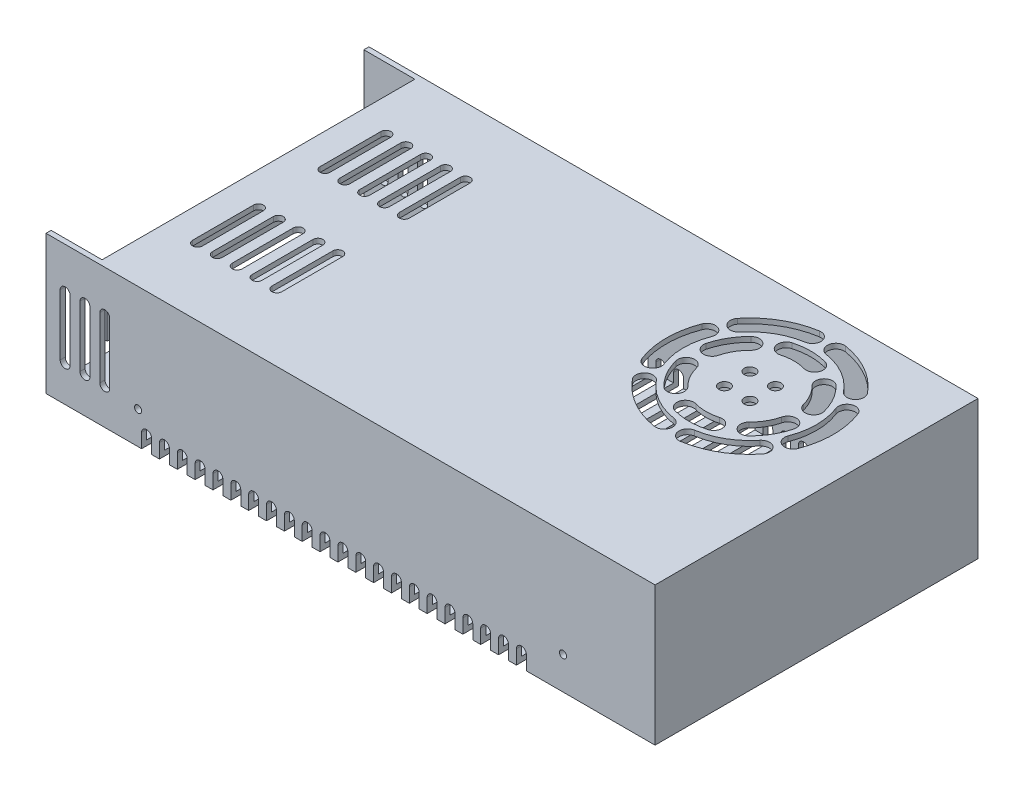
SolidWorks part; units mm, degrees
material "6061 Alloy"
ref_plane "Front Plane" through (0, 0, 0) normal (0, 0, 1) x (1, 0, 0)
ref_plane "Top Plane" through (0, 0, 0) normal (0, 1, 0) x (1, 0, 0)
ref_plane "Right Plane" through (0, 0, 0) normal (1, 0, 0) x (0, 0, -1)
sketch "Sketch1" plane through (0, 0, 0) normal (0, 1, 0) x (1, 0, 0)
  line L0 (-107.5, 55.2) -> (105.7, 55.2)
  line L1 (-107.5, -57) -> (107.5, -57)
  line L2 (-107.5, -57) -> (-107.5, -55.2)
  line L3 (-107.5, 57) -> (107.5, 57)
  line L4 (107.5, -57) -> (107.5, 57)
  line L5 (-107.5, -57) -> (107.5, 57) construction
  line L6 (-107.5, 57) -> (107.5, -57) construction
  line L7 (105.7, 55.2) -> (105.7, -55.2)
  line L8 (105.7, -55.2) -> (-107.5, -55.2)
  line L9 (-107.5, 55.2) -> (-107.5, 57)
  point P0 (0, 0)
  dimension "D1" = 114
  dimension "D2" = 215
  dimension "D3" = 1.8
  dimension "D4" = 1.8
  dimension "D5" = 1.8
extrude "Boss-Extrude1" add sketch "Sketch1" along normal blind 49
sketch "Sketch2" plane through (0, 0, 0) normal (0, 1, 0) x (1, 0, 0)
  line L0 (107.5, -57) -> (107.5, 57)
  line L1 (107.5, -57) -> (-107.5, -57)
  line L2 (107.5, 57) -> (-107.5, 57)
  line L3 (-107.5, -57) -> (-107.5, 57)
extrude "Boss-Extrude2" add sketch "Sketch2" along normal blind 1.8
sketch "Sketch3" plane through (0, 49, 0) normal (0, 1, 0) x (1, 0, 0)
  line L0 (107.5, 57) -> (107.5, -57)
  line L1 (107.5, 57) -> (-89.5, 57)
  line L2 (107.5, -57) -> (-89.5, -57)
  line L3 (-89.5, 57) -> (-89.5, -57)
  line L4 (-107.5, -55.2) -> (-107.5, -57) construction
  dimension "D1" = 18
extrude "Boss-Extrude3" add sketch "Sketch3" against normal blind 1.8
sketch "Sketch4" plane through (0, 49, 0) normal (0, 1, 0) x (1, 0, 0)
  line L0 (-89.5, 55.2) -> (-89.5, -55.2)
  line L1 (-89.5, 55.2) -> (-87.7, 55.2)
  line L2 (-89.5, -55.2) -> (-87.7, -55.2)
  line L3 (-87.7, 55.2) -> (-87.7, -55.2)
  dimension "D1" = 1.8
extrude "Boss-Extrude4" add sketch "Sketch4" against normal blind 24
sketch "Sketch5" plane through (0, 49, 0) normal (0, 1, 0) x (1, 0, 0)
  line L0 (-79.5, -11.75) -> (-79.5, -33.25)
  line L1 (-76, -33.25) -> (-76, -11.75)
  line L2 (-107.5, 0) -> (107.5, 0) construction
  line L3 (-107.5, 55.2) -> (-107.5, -55.2) construction
  line L4 (107.5, -57) -> (107.5, 57) construction
  line L5 (-89.5, 55.2) -> (-89.5, -55.2) construction
  line L6 (-72.5, -11.75) -> (-72.5, -33.25)
  line L7 (-69, -33.25) -> (-69, -11.75)
  line L8 (-65.5, -11.75) -> (-65.5, -33.25)
  line L9 (-62, -33.25) -> (-62, -11.75)
  line L10 (-58.5, -11.75) -> (-58.5, -33.25)
  line L11 (-55, -33.25) -> (-55, -11.75)
  line L12 (-51.5, -11.75) -> (-51.5, -33.25)
  line L13 (-48, -33.25) -> (-48, -11.75)
  line L14 (-48, 33.25) -> (-48, 11.75)
  line L15 (-51.5, 11.75) -> (-51.5, 33.25)
  line L16 (-55, 33.25) -> (-55, 11.75)
  line L17 (-58.5, 11.75) -> (-58.5, 33.25)
  line L18 (-62, 33.25) -> (-62, 11.75)
  line L19 (-65.5, 11.75) -> (-65.5, 33.25)
  line L20 (-69, 33.25) -> (-69, 11.75)
  line L21 (-72.5, 11.75) -> (-72.5, 33.25)
  line L22 (-76, 33.25) -> (-76, 11.75)
  line L23 (-79.5, 11.75) -> (-79.5, 33.25)
  arc A0 (-76, -11.75) -> (-79.5, -11.75) centre (-77.75, -11.75) ccw
  arc A1 (-79.5, -33.25) -> (-76, -33.25) centre (-77.75, -33.25) ccw
  arc A2 (-69, -11.75) -> (-72.5, -11.75) centre (-70.75, -11.75) ccw
  arc A3 (-72.5, -33.25) -> (-69, -33.25) centre (-70.75, -33.25) ccw
  arc A4 (-62, -11.75) -> (-65.5, -11.75) centre (-63.75, -11.75) ccw
  arc A5 (-65.5, -33.25) -> (-62, -33.25) centre (-63.75, -33.25) ccw
  arc A6 (-55, -11.75) -> (-58.5, -11.75) centre (-56.75, -11.75) ccw
  arc A7 (-58.5, -33.25) -> (-55, -33.25) centre (-56.75, -33.25) ccw
  arc A8 (-48, -11.75) -> (-51.5, -11.75) centre (-49.75, -11.75) ccw
  arc A9 (-51.5, -33.25) -> (-48, -33.25) centre (-49.75, -33.25) ccw
  arc A10 (-51.5, 33.25) -> (-48, 33.25) centre (-49.75, 33.25) cw
  arc A11 (-48, 11.75) -> (-51.5, 11.75) centre (-49.75, 11.75) cw
  arc A12 (-58.5, 33.25) -> (-55, 33.25) centre (-56.75, 33.25) cw
  arc A13 (-55, 11.75) -> (-58.5, 11.75) centre (-56.75, 11.75) cw
  arc A14 (-65.5, 33.25) -> (-62, 33.25) centre (-63.75, 33.25) cw
  arc A15 (-62, 11.75) -> (-65.5, 11.75) centre (-63.75, 11.75) cw
  arc A16 (-72.5, 33.25) -> (-69, 33.25) centre (-70.75, 33.25) cw
  arc A17 (-69, 11.75) -> (-72.5, 11.75) centre (-70.75, 11.75) cw
  arc A18 (-79.5, 33.25) -> (-76, 33.25) centre (-77.75, 33.25) cw
  arc A19 (-76, 11.75) -> (-79.5, 11.75) centre (-77.75, 11.75) cw
  dimension "D1" = 3.5
  dimension "D2" = 21.5
  dimension "D3" = 11.75
  dimension "D4" = 10
  dimension "D5" = 5
extrude "Cut-Extrude1" cut sketch "Sketch5" against normal up to surface (1.8 mm away) up to face at (9, 47.2, 0)
sketch "Sketch6" plane through (0, 0, -57) normal (0, 0, -1) x (-1, 0, 0)
  line L0 (102.5, 34.25) -> (102.5, 12.75)
  line L1 (99, 34.25) -> (99, 12.75)
  line L2 (-107.5, 0) -> (107.5, 0) construction
  line L3 (107.5, 49) -> (107.5, 0) construction
  line L4 (92, 34.25) -> (92, 12.75)
  line L5 (95.5, 34.25) -> (95.5, 12.75)
  line L6 (85, 34.25) -> (85, 12.75)
  line L7 (88.5, 34.25) -> (88.5, 12.75)
  line L8 (73.75, 5) -> (73.75, 0)
  line L9 (73.75, 0) -> (70.25, 0)
  line L10 (70.25, 0) -> (70.25, 5)
  line L11 (67.45, 5) -> (67.45, 0)
  line L12 (63.95, 0) -> (63.95, 5)
  line L13 (67.45, 0) -> (63.95, 0)
  line L14 (61.15, 5) -> (61.15, 0)
  line L15 (57.65, 0) -> (57.65, 5)
  line L16 (61.15, 0) -> (57.65, 0)
  line L17 (54.85, 5) -> (54.85, 0)
  line L18 (51.35, 0) -> (51.35, 5)
  line L19 (54.85, 0) -> (51.35, 0)
  line L20 (48.55, 5) -> (48.55, 0)
  line L21 (45.05, 0) -> (45.05, 5)
  line L22 (48.55, 0) -> (45.05, 0)
  line L23 (42.25, 5) -> (42.25, 0)
  line L24 (38.75, 0) -> (38.75, 5)
  line L25 (42.25, 0) -> (38.75, 0)
  line L26 (35.95, 5) -> (35.95, 0)
  line L27 (32.45, 0) -> (32.45, 5)
  line L28 (35.95, 0) -> (32.45, 0)
  line L29 (29.65, 5) -> (29.65, 0)
  line L30 (26.15, 0) -> (26.15, 5)
  line L31 (29.65, 0) -> (26.15, 0)
  line L32 (23.35, 5) -> (23.35, 0)
  line L33 (19.85, 0) -> (19.85, 5)
  line L34 (23.35, 0) -> (19.85, 0)
  line L35 (17.05, 5) -> (17.05, 0)
  line L36 (13.55, 0) -> (13.55, 5)
  line L37 (17.05, 0) -> (13.55, 0)
  line L38 (10.75, 5) -> (10.75, 0)
  line L39 (7.25, 0) -> (7.25, 5)
  line L40 (10.75, 0) -> (7.25, 0)
  line L41 (4.45, 5) -> (4.45, 0)
  line L42 (0.95, 0) -> (0.95, 5)
  line L43 (4.45, 0) -> (0.95, 0)
  line L44 (-1.85, 5) -> (-1.85, 0)
  line L45 (-5.35, 0) -> (-5.35, 5)
  line L46 (-1.85, 0) -> (-5.35, 0)
  line L47 (-8.15, 5) -> (-8.15, 0)
  line L48 (-11.65, 0) -> (-11.65, 5)
  line L49 (-8.15, 0) -> (-11.65, 0)
  line L50 (-14.45, 5) -> (-14.45, 0)
  line L51 (-17.95, 0) -> (-17.95, 5)
  line L52 (-14.45, 0) -> (-17.95, 0)
  line L53 (-20.75, 5) -> (-20.75, 0)
  line L54 (-24.25, 0) -> (-24.25, 5)
  line L55 (-20.75, 0) -> (-24.25, 0)
  line L56 (-27.05, 5) -> (-27.05, 0)
  line L57 (-30.55, 0) -> (-30.55, 5)
  line L58 (-27.05, 0) -> (-30.55, 0)
  line L59 (-33.35, 5) -> (-33.35, 0)
  line L60 (-36.85, 0) -> (-36.85, 5)
  line L61 (-33.35, 0) -> (-36.85, 0)
  line L62 (-39.65, 5) -> (-39.65, 0)
  line L63 (-43.15, 0) -> (-43.15, 5)
  line L64 (-39.65, 0) -> (-43.15, 0)
  line L65 (-45.95, 5) -> (-45.95, 0)
  line L66 (-49.45, 0) -> (-49.45, 5)
  line L67 (-45.95, 0) -> (-49.45, 0)
  line L68 (-52.25, 5) -> (-52.25, 0)
  line L69 (-55.75, 0) -> (-55.75, 5)
  line L70 (-52.25, 0) -> (-55.75, 0)
  line L71 (-58.55, 5) -> (-58.55, 0)
  line L72 (-62.05, 0) -> (-62.05, 5)
  line L73 (-58.55, 0) -> (-62.05, 0)
  arc A0 (102.5, 34.25) -> (99, 34.25) centre (100.75, 34.25) ccw
  arc A1 (99, 12.75) -> (102.5, 12.75) centre (100.75, 12.75) ccw
  arc A2 (95.5, 34.25) -> (92, 34.25) centre (93.75, 34.25) ccw
  arc A3 (92, 12.75) -> (95.5, 12.75) centre (93.75, 12.75) ccw
  arc A4 (88.5, 34.25) -> (85, 34.25) centre (86.75, 34.25) ccw
  arc A5 (85, 12.75) -> (88.5, 12.75) centre (86.75, 12.75) ccw
  arc A6 (73.75, 5) -> (70.25, 5) centre (72, 5) ccw
  arc A7 (67.45, 5) -> (63.95, 5) centre (65.7, 5) ccw
  arc A8 (61.15, 5) -> (57.65, 5) centre (59.4, 5) ccw
  arc A9 (54.85, 5) -> (51.35, 5) centre (53.1, 5) ccw
  arc A10 (48.55, 5) -> (45.05, 5) centre (46.8, 5) ccw
  arc A11 (42.25, 5) -> (38.75, 5) centre (40.5, 5) ccw
  arc A12 (35.95, 5) -> (32.45, 5) centre (34.2, 5) ccw
  arc A13 (29.65, 5) -> (26.15, 5) centre (27.9, 5) ccw
  arc A14 (23.35, 5) -> (19.85, 5) centre (21.6, 5) ccw
  arc A15 (17.05, 5) -> (13.55, 5) centre (15.3, 5) ccw
  arc A16 (10.75, 5) -> (7.25, 5) centre (9, 5) ccw
  arc A17 (4.45, 5) -> (0.95, 5) centre (2.7, 5) ccw
  arc A18 (-1.85, 5) -> (-5.35, 5) centre (-3.6, 5) ccw
  arc A19 (-8.15, 5) -> (-11.65, 5) centre (-9.9, 5) ccw
  arc A20 (-14.45, 5) -> (-17.95, 5) centre (-16.2, 5) ccw
  arc A21 (-20.75, 5) -> (-24.25, 5) centre (-22.5, 5) ccw
  arc A22 (-27.05, 5) -> (-30.55, 5) centre (-28.8, 5) ccw
  arc A23 (-33.35, 5) -> (-36.85, 5) centre (-35.1, 5) ccw
  arc A24 (-39.65, 5) -> (-43.15, 5) centre (-41.4, 5) ccw
  arc A25 (-45.95, 5) -> (-49.45, 5) centre (-47.7, 5) ccw
  arc A26 (-52.25, 5) -> (-55.75, 5) centre (-54, 5) ccw
  arc A27 (-58.55, 5) -> (-62.05, 5) centre (-60.3, 5) ccw
  dimension "D1" = 3.5
  dimension "D6" = 3.5
  dimension "D7" = 5
  dimension "D2" = 21.5
  dimension "D3" = 12.75
  dimension "D4" = 5
  dimension "D8" = 35.5
  dimension "D5" = 3
  dimension "D9" = 22
extrude "Cut-Extrude2" cut sketch "Sketch6" against normal up to surface (1.8 mm away) up to face at (-44.75, 30.75, -55.2)
sketch "Sketch7" plane through (0, 0, 57) normal (0, 0, 1) x (1, 0, 0)
  line L8 (-102.5, 34.25) -> (-102.5, 12.75)
  line L9 (-99, 12.75) -> (-99, 34.25)
  line L10 (-102.5, 34.25) -> (-102.5, 12.75)
  line L11 (-99, 12.75) -> (-99, 34.25)
  line L12 (-85, 12.75) -> (-85, 34.25)
  line L13 (-73.75, 5) -> (-73.75, 0)
  line L14 (-73.75, 0) -> (-70.25, 0)
  line L15 (-70.25, 0) -> (-70.25, 5)
  line L16 (-73.75, 5) -> (-73.75, 0)
  line L17 (-73.75, 0) -> (-70.25, 0)
  line L18 (-70.25, 0) -> (-70.25, 5)
  line L19 (-88.5, 34.25) -> (-88.5, 12.75)
  line L20 (-85, 12.75) -> (-85, 34.25)
  line L21 (-88.5, 34.25) -> (-88.5, 12.75)
  line L22 (-92, 12.75) -> (-92, 34.25)
  line L23 (-95.5, 34.25) -> (-95.5, 12.75)
  line L24 (-92, 12.75) -> (-92, 34.25)
  line L25 (-95.5, 34.25) -> (-95.5, 12.75)
  line L27 (-54.85, 5) -> (-54.85, 0)
  line L28 (-54.85, 0) -> (-51.35, 0)
  line L29 (-51.35, 0) -> (-51.35, 5)
  line L30 (-54.85, 5) -> (-54.85, 0)
  line L31 (-54.85, 0) -> (-51.35, 0)
  line L32 (-51.35, 0) -> (-51.35, 5)
  line L33 (-61.15, 5) -> (-61.15, 0)
  line L34 (-61.15, 0) -> (-57.65, 0)
  line L35 (-57.65, 0) -> (-57.65, 5)
  line L36 (-61.15, 5) -> (-61.15, 0)
  line L37 (-61.15, 0) -> (-57.65, 0)
  line L38 (-57.65, 0) -> (-57.65, 5)
  line L39 (-63.95, 0) -> (-63.95, 5)
  line L40 (-67.45, 5) -> (-67.45, 0)
  line L41 (-67.45, 0) -> (-63.95, 0)
  line L42 (-63.95, 0) -> (-63.95, 5)
  line L43 (-67.45, 5) -> (-67.45, 0)
  line L44 (-67.45, 0) -> (-63.95, 0)
  line L45 (-29.65, 5) -> (-29.65, 0)
  line L46 (-29.65, 0) -> (-26.15, 0)
  line L47 (-26.15, 0) -> (-26.15, 5)
  line L48 (-29.65, 5) -> (-29.65, 0)
  line L49 (-29.65, 0) -> (-26.15, 0)
  line L50 (-26.15, 0) -> (-26.15, 5)
  line L51 (-35.95, 5) -> (-35.95, 0)
  line L52 (-35.95, 0) -> (-32.45, 0)
  line L53 (-32.45, 0) -> (-32.45, 5)
  line L54 (-35.95, 5) -> (-35.95, 0)
  line L55 (-35.95, 0) -> (-32.45, 0)
  line L56 (-32.45, 0) -> (-32.45, 5)
  line L57 (-42.25, 5) -> (-42.25, 0)
  line L58 (-42.25, 0) -> (-38.75, 0)
  line L59 (-38.75, 0) -> (-38.75, 5)
  line L60 (-42.25, 5) -> (-42.25, 0)
  line L61 (-42.25, 0) -> (-38.75, 0)
  line L62 (-38.75, 0) -> (-38.75, 5)
  line L63 (-45.05, 0) -> (-45.05, 5)
  line L64 (-48.55, 0) -> (-45.05, 0)
  line L65 (-48.55, 5) -> (-48.55, 0)
  line L66 (-45.05, 0) -> (-45.05, 5)
  line L67 (-48.55, 0) -> (-45.05, 0)
  line L68 (-48.55, 5) -> (-48.55, 0)
  line L69 (-10.75, 5) -> (-10.75, 0)
  line L70 (-10.75, 0) -> (-7.25, 0)
  line L71 (-7.25, 0) -> (-7.25, 5)
  line L72 (-10.75, 5) -> (-10.75, 0)
  line L73 (-10.75, 0) -> (-7.25, 0)
  line L74 (-7.25, 0) -> (-7.25, 5)
  line L75 (-17.05, 5) -> (-17.05, 0)
  line L76 (-17.05, 0) -> (-13.55, 0)
  line L77 (-13.55, 0) -> (-13.55, 5)
  line L78 (-17.05, 5) -> (-17.05, 0)
  line L79 (-17.05, 0) -> (-13.55, 0)
  line L80 (-13.55, 0) -> (-13.55, 5)
  line L81 (-23.35, 5) -> (-23.35, 0)
  line L82 (-23.35, 0) -> (-19.85, 0)
  line L83 (-19.85, 0) -> (-19.85, 5)
  line L84 (-23.35, 5) -> (-23.35, 0)
  line L85 (-23.35, 0) -> (-19.85, 0)
  line L86 (-19.85, 0) -> (-19.85, 5)
  line L87 (8.15, 5) -> (8.15, 0)
  line L88 (8.15, 0) -> (11.65, 0)
  line L89 (11.65, 0) -> (11.65, 5)
  line L90 (8.15, 5) -> (8.15, 0)
  line L91 (8.15, 0) -> (11.65, 0)
  line L92 (11.65, 0) -> (11.65, 5)
  line L93 (1.85, 5) -> (1.85, 0)
  line L94 (1.85, 0) -> (5.35, 0)
  line L95 (5.35, 0) -> (5.35, 5)
  line L96 (1.85, 5) -> (1.85, 0)
  line L97 (1.85, 0) -> (5.35, 0)
  line L98 (5.35, 0) -> (5.35, 5)
  line L99 (-4.45, 5) -> (-4.45, 0)
  line L100 (-4.45, 0) -> (-0.95, 0)
  line L101 (-0.95, 0) -> (-0.95, 5)
  line L102 (-4.45, 5) -> (-4.45, 0)
  line L103 (-4.45, 0) -> (-0.95, 0)
  line L104 (-0.95, 0) -> (-0.95, 5)
  line L105 (27.05, 5) -> (27.05, 0)
  line L106 (27.05, 0) -> (30.55, 0)
  line L107 (30.55, 0) -> (30.55, 5)
  line L108 (27.05, 5) -> (27.05, 0)
  line L109 (27.05, 0) -> (30.55, 0)
  line L110 (30.55, 0) -> (30.55, 5)
  line L111 (20.75, 5) -> (20.75, 0)
  line L112 (20.75, 0) -> (24.25, 0)
  line L113 (24.25, 0) -> (24.25, 5)
  line L114 (20.75, 5) -> (20.75, 0)
  line L115 (20.75, 0) -> (24.25, 0)
  line L116 (24.25, 0) -> (24.25, 5)
  line L117 (14.45, 5) -> (14.45, 0)
  line L118 (17.95, 0) -> (17.95, 5)
  line L119 (14.45, 0) -> (17.95, 0)
  line L120 (14.45, 5) -> (14.45, 0)
  line L121 (17.95, 0) -> (17.95, 5)
  line L122 (14.45, 0) -> (17.95, 0)
  line L123 (45.95, 5) -> (45.95, 0)
  line L124 (45.95, 0) -> (49.45, 0)
  line L125 (49.45, 0) -> (49.45, 5)
  line L126 (45.95, 5) -> (45.95, 0)
  line L127 (45.95, 0) -> (49.45, 0)
  line L128 (49.45, 0) -> (49.45, 5)
  line L129 (39.65, 5) -> (39.65, 0)
  line L130 (39.65, 0) -> (43.15, 0)
  line L131 (43.15, 0) -> (43.15, 5)
  line L132 (39.65, 5) -> (39.65, 0)
  line L133 (39.65, 0) -> (43.15, 0)
  line L134 (43.15, 0) -> (43.15, 5)
  line L135 (36.85, 0) -> (36.85, 5)
  line L136 (33.35, 5) -> (33.35, 0)
  line L137 (33.35, 0) -> (36.85, 0)
  line L138 (36.85, 0) -> (36.85, 5)
  line L139 (33.35, 5) -> (33.35, 0)
  line L140 (33.35, 0) -> (36.85, 0)
  line L141 (58.55, 5) -> (58.55, 0)
  line L142 (58.55, 0) -> (62.05, 0)
  line L143 (62.05, 0) -> (62.05, 5)
  line L144 (58.55, 5) -> (58.55, 0)
  line L145 (58.55, 0) -> (62.05, 0)
  line L146 (62.05, 0) -> (62.05, 5)
  line L147 (55.75, 0) -> (55.75, 5)
  line L148 (52.25, 0) -> (55.75, 0)
  line L149 (52.25, 5) -> (52.25, 0)
  line L150 (55.75, 0) -> (55.75, 5)
  line L151 (52.25, 0) -> (55.75, 0)
  line L152 (52.25, 5) -> (52.25, 0)
  arc A7 (-70.25, 5) -> (-73.75, 5) centre (-72, 5) ccw
  arc A8 (-102.5, 12.75) -> (-99, 12.75) centre (-100.75, 12.75) ccw
  arc A9 (-99, 34.25) -> (-102.5, 34.25) centre (-100.75, 34.25) ccw
  arc A10 (-102.5, 12.75) -> (-99, 12.75) centre (-100.75, 12.75) ccw
  arc A11 (-99, 34.25) -> (-102.5, 34.25) centre (-100.75, 34.25) ccw
  arc A12 (-70.25, 5) -> (-73.75, 5) centre (-72, 5) ccw
  arc A13 (-51.35, 5) -> (-54.85, 5) centre (-53.1, 5) ccw
  arc A14 (-88.5, 12.75) -> (-85, 12.75) centre (-86.75, 12.75) ccw
  arc A15 (-85, 34.25) -> (-88.5, 34.25) centre (-86.75, 34.25) ccw
  arc A16 (-88.5, 12.75) -> (-85, 12.75) centre (-86.75, 12.75) ccw
  arc A17 (-85, 34.25) -> (-88.5, 34.25) centre (-86.75, 34.25) ccw
  arc A18 (-92, 34.25) -> (-95.5, 34.25) centre (-93.75, 34.25) ccw
  arc A19 (-95.5, 12.75) -> (-92, 12.75) centre (-93.75, 12.75) ccw
  arc A20 (-92, 34.25) -> (-95.5, 34.25) centre (-93.75, 34.25) ccw
  arc A21 (-95.5, 12.75) -> (-92, 12.75) centre (-93.75, 12.75) ccw
  arc A22 (-51.35, 5) -> (-54.85, 5) centre (-53.1, 5) ccw
  arc A23 (-57.65, 5) -> (-61.15, 5) centre (-59.4, 5) ccw
  arc A24 (-57.65, 5) -> (-61.15, 5) centre (-59.4, 5) ccw
  arc A25 (-63.95, 5) -> (-67.45, 5) centre (-65.7, 5) ccw
  arc A26 (-63.95, 5) -> (-67.45, 5) centre (-65.7, 5) ccw
  arc A27 (-26.15, 5) -> (-29.65, 5) centre (-27.9, 5) ccw
  arc A28 (-26.15, 5) -> (-29.65, 5) centre (-27.9, 5) ccw
  arc A29 (-32.45, 5) -> (-35.95, 5) centre (-34.2, 5) ccw
  arc A30 (-32.45, 5) -> (-35.95, 5) centre (-34.2, 5) ccw
  arc A31 (-38.75, 5) -> (-42.25, 5) centre (-40.5, 5) ccw
  arc A32 (-38.75, 5) -> (-42.25, 5) centre (-40.5, 5) ccw
  arc A33 (-45.05, 5) -> (-48.55, 5) centre (-46.8, 5) ccw
  arc A34 (-45.05, 5) -> (-48.55, 5) centre (-46.8, 5) ccw
  arc A35 (-7.25, 5) -> (-10.75, 5) centre (-9, 5) ccw
  arc A36 (-7.25, 5) -> (-10.75, 5) centre (-9, 5) ccw
  arc A37 (-13.55, 5) -> (-17.05, 5) centre (-15.3, 5) ccw
  arc A38 (-13.55, 5) -> (-17.05, 5) centre (-15.3, 5) ccw
  arc A39 (-19.85, 5) -> (-23.35, 5) centre (-21.6, 5) ccw
  arc A40 (-19.85, 5) -> (-23.35, 5) centre (-21.6, 5) ccw
  arc A41 (11.65, 5) -> (8.15, 5) centre (9.9, 5) ccw
  arc A42 (11.65, 5) -> (8.15, 5) centre (9.9, 5) ccw
  arc A43 (5.35, 5) -> (1.85, 5) centre (3.6, 5) ccw
  arc A44 (5.35, 5) -> (1.85, 5) centre (3.6, 5) ccw
  arc A45 (-0.95, 5) -> (-4.45, 5) centre (-2.7, 5) ccw
  arc A46 (-0.95, 5) -> (-4.45, 5) centre (-2.7, 5) ccw
  arc A47 (30.55, 5) -> (27.05, 5) centre (28.8, 5) ccw
  arc A48 (30.55, 5) -> (27.05, 5) centre (28.8, 5) ccw
  arc A49 (24.25, 5) -> (20.75, 5) centre (22.5, 5) ccw
  arc A50 (24.25, 5) -> (20.75, 5) centre (22.5, 5) ccw
  arc A51 (17.95, 5) -> (14.45, 5) centre (16.2, 5) ccw
  arc A52 (17.95, 5) -> (14.45, 5) centre (16.2, 5) ccw
  arc A53 (49.45, 5) -> (45.95, 5) centre (47.7, 5) ccw
  arc A54 (49.45, 5) -> (45.95, 5) centre (47.7, 5) ccw
  arc A55 (43.15, 5) -> (39.65, 5) centre (41.4, 5) ccw
  arc A56 (43.15, 5) -> (39.65, 5) centre (41.4, 5) ccw
  arc A57 (36.85, 5) -> (33.35, 5) centre (35.1, 5) ccw
  arc A58 (36.85, 5) -> (33.35, 5) centre (35.1, 5) ccw
  arc A59 (62.05, 5) -> (58.55, 5) centre (60.3, 5) ccw
  arc A60 (62.05, 5) -> (58.55, 5) centre (60.3, 5) ccw
  arc A61 (55.75, 5) -> (52.25, 5) centre (54, 5) ccw
  arc A62 (55.75, 5) -> (52.25, 5) centre (54, 5) ccw
  dimension "D1" = 0
  dimension "D2" = 0
  dimension "D3" = 0
  dimension "D4" = 0
  dimension "D5" = 0
  dimension "D6" = 0
  dimension "D7" = 0
  dimension "D8" = 0
  dimension "D9" = 0
  dimension "D10" = 0
  dimension "D11" = 0
  dimension "D12" = 0
  dimension "D13" = 0
  dimension "D14" = 0
  dimension "D15" = 0
  dimension "D16" = 0
  dimension "D17" = 0
  dimension "D18" = 0
  dimension "D19" = 0
  dimension "D20" = 0
  dimension "D21" = 0
  dimension "D22" = 0
  dimension "D23" = 0
  dimension "D24" = 0
  dimension "D25" = 0
extrude "Cut-Extrude3" cut sketch "Sketch7" against normal up to surface (1.8 mm away) up to face at (-44.75, 30.75, 55.2)
sketch "Sketch14" plane through (0, 0, 0) normal (0, -1, 0) x (1, 0, 0)
  line L0 (-73.75, -55.2) -> (-73.75, -36.95)
  line L1 (-73.75, -55.2) -> (-70.25, -55.2)
  line L2 (-70.25, -36.95) -> (-70.25, -55.2)
  line L3 (-67.45, -55.2) -> (-67.45, -36.95)
  line L4 (-63.95, -36.95) -> (-63.95, -55.2)
  line L5 (-67.45, -55.2) -> (-63.95, -55.2)
  line L6 (-61.15, -55.2) -> (-61.15, -36.95)
  line L7 (-57.65, -36.95) -> (-57.65, -55.2)
  line L8 (-61.15, -55.2) -> (-57.65, -55.2)
  line L9 (-54.85, -55.2) -> (-54.85, -36.95)
  line L10 (-51.35, -36.95) -> (-51.35, -55.2)
  line L11 (-54.85, -55.2) -> (-51.35, -55.2)
  line L12 (-48.55, -55.2) -> (-48.55, -36.95)
  line L13 (-45.05, -36.95) -> (-45.05, -55.2)
  line L14 (-48.55, -55.2) -> (-45.05, -55.2)
  line L15 (-42.25, -55.2) -> (-42.25, -36.95)
  line L16 (-38.75, -36.95) -> (-38.75, -55.2)
  line L17 (-42.25, -55.2) -> (-38.75, -55.2)
  line L18 (-35.95, -55.2) -> (-35.95, -36.95)
  line L19 (-32.45, -36.95) -> (-32.45, -55.2)
  line L20 (-35.95, -55.2) -> (-32.45, -55.2)
  line L21 (-29.65, -55.2) -> (-29.65, -36.95)
  line L22 (-26.15, -36.95) -> (-26.15, -55.2)
  line L23 (-29.65, -55.2) -> (-26.15, -55.2)
  line L24 (-23.35, -55.2) -> (-23.35, -36.95)
  line L25 (-19.85, -36.95) -> (-19.85, -55.2)
  line L26 (-23.35, -55.2) -> (-19.85, -55.2)
  line L27 (-17.05, -55.2) -> (-17.05, -36.95)
  line L28 (-13.55, -36.95) -> (-13.55, -55.2)
  line L29 (-17.05, -55.2) -> (-13.55, -55.2)
  line L30 (-10.75, -55.2) -> (-10.75, -36.95)
  line L31 (-7.25, -36.95) -> (-7.25, -55.2)
  line L32 (-10.75, -55.2) -> (-7.25, -55.2)
  line L33 (-4.45, -55.2) -> (-4.45, -36.95)
  line L34 (-0.95, -36.95) -> (-0.95, -55.2)
  line L35 (-4.45, -55.2) -> (-0.95, -55.2)
  line L36 (1.85, -55.2) -> (1.85, -36.95)
  line L37 (5.35, -36.95) -> (5.35, -55.2)
  line L38 (1.85, -55.2) -> (5.35, -55.2)
  line L39 (8.15, -55.2) -> (8.15, -36.95)
  line L40 (11.65, -36.95) -> (11.65, -55.2)
  line L41 (8.15, -55.2) -> (11.65, -55.2)
  line L42 (14.45, -55.2) -> (14.45, -36.95)
  line L43 (17.95, -36.95) -> (17.95, -55.2)
  line L44 (14.45, -55.2) -> (17.95, -55.2)
  line L45 (20.75, -55.2) -> (20.75, -36.95)
  line L46 (24.25, -36.95) -> (24.25, -55.2)
  line L47 (20.75, -55.2) -> (24.25, -55.2)
  line L48 (27.05, -55.2) -> (27.05, -36.95)
  line L49 (30.55, -36.95) -> (30.55, -55.2)
  line L50 (27.05, -55.2) -> (30.55, -55.2)
  line L51 (33.35, -55.2) -> (33.35, -36.95)
  line L52 (36.85, -36.95) -> (36.85, -55.2)
  line L53 (33.35, -55.2) -> (36.85, -55.2)
  line L54 (39.65, -55.2) -> (39.65, -36.95)
  line L55 (43.15, -36.95) -> (43.15, -55.2)
  line L56 (39.65, -55.2) -> (43.15, -55.2)
  line L57 (45.95, -55.2) -> (45.95, -36.95)
  line L58 (49.45, -36.95) -> (49.45, -55.2)
  line L59 (45.95, -55.2) -> (49.45, -55.2)
  line L60 (52.25, -55.2) -> (52.25, -36.95)
  line L61 (55.75, -36.95) -> (55.75, -55.2)
  line L62 (52.25, -55.2) -> (55.75, -55.2)
  line L63 (58.55, -55.2) -> (58.55, -36.95)
  line L64 (62.05, -36.95) -> (62.05, -55.2)
  line L65 (58.55, -55.2) -> (62.05, -55.2)
  line L66 (-107.5, 0) -> (107.5, 0) construction
  line L67 (-107.5, -57) -> (-107.5, 57) construction
  line L68 (107.5, 57) -> (107.5, -57) construction
  line L69 (58.55, 55.2) -> (62.05, 55.2)
  line L70 (62.05, 36.95) -> (62.05, 55.2)
  line L71 (58.55, 55.2) -> (58.55, 36.95)
  line L72 (52.25, 55.2) -> (55.75, 55.2)
  line L73 (55.75, 36.95) -> (55.75, 55.2)
  line L74 (52.25, 55.2) -> (52.25, 36.95)
  line L75 (45.95, 55.2) -> (49.45, 55.2)
  line L76 (49.45, 36.95) -> (49.45, 55.2)
  line L77 (45.95, 55.2) -> (45.95, 36.95)
  line L78 (39.65, 55.2) -> (43.15, 55.2)
  line L79 (43.15, 36.95) -> (43.15, 55.2)
  line L80 (39.65, 55.2) -> (39.65, 36.95)
  line L81 (33.35, 55.2) -> (36.85, 55.2)
  line L82 (36.85, 36.95) -> (36.85, 55.2)
  line L83 (33.35, 55.2) -> (33.35, 36.95)
  line L84 (27.05, 55.2) -> (30.55, 55.2)
  line L85 (30.55, 36.95) -> (30.55, 55.2)
  line L86 (27.05, 55.2) -> (27.05, 36.95)
  line L87 (20.75, 55.2) -> (24.25, 55.2)
  line L88 (24.25, 36.95) -> (24.25, 55.2)
  line L89 (20.75, 55.2) -> (20.75, 36.95)
  line L90 (14.45, 55.2) -> (17.95, 55.2)
  line L91 (17.95, 36.95) -> (17.95, 55.2)
  line L92 (14.45, 55.2) -> (14.45, 36.95)
  line L93 (8.15, 55.2) -> (11.65, 55.2)
  line L94 (11.65, 36.95) -> (11.65, 55.2)
  line L95 (8.15, 55.2) -> (8.15, 36.95)
  line L96 (1.85, 55.2) -> (5.35, 55.2)
  line L97 (5.35, 36.95) -> (5.35, 55.2)
  line L98 (1.85, 55.2) -> (1.85, 36.95)
  line L99 (-4.45, 55.2) -> (-0.95, 55.2)
  line L100 (-0.95, 36.95) -> (-0.95, 55.2)
  line L101 (-4.45, 55.2) -> (-4.45, 36.95)
  line L102 (-10.75, 55.2) -> (-7.25, 55.2)
  line L103 (-7.25, 36.95) -> (-7.25, 55.2)
  line L104 (-10.75, 55.2) -> (-10.75, 36.95)
  line L105 (-17.05, 55.2) -> (-13.55, 55.2)
  line L106 (-13.55, 36.95) -> (-13.55, 55.2)
  line L107 (-17.05, 55.2) -> (-17.05, 36.95)
  line L108 (-23.35, 55.2) -> (-19.85, 55.2)
  line L109 (-19.85, 36.95) -> (-19.85, 55.2)
  line L110 (-23.35, 55.2) -> (-23.35, 36.95)
  line L111 (-29.65, 55.2) -> (-26.15, 55.2)
  line L112 (-26.15, 36.95) -> (-26.15, 55.2)
  line L113 (-29.65, 55.2) -> (-29.65, 36.95)
  line L114 (-35.95, 55.2) -> (-32.45, 55.2)
  line L115 (-32.45, 36.95) -> (-32.45, 55.2)
  line L116 (-35.95, 55.2) -> (-35.95, 36.95)
  line L117 (-42.25, 55.2) -> (-38.75, 55.2)
  line L118 (-38.75, 36.95) -> (-38.75, 55.2)
  line L119 (-42.25, 55.2) -> (-42.25, 36.95)
  line L120 (-48.55, 55.2) -> (-45.05, 55.2)
  line L121 (-45.05, 36.95) -> (-45.05, 55.2)
  line L122 (-48.55, 55.2) -> (-48.55, 36.95)
  line L123 (-54.85, 55.2) -> (-51.35, 55.2)
  line L124 (-51.35, 36.95) -> (-51.35, 55.2)
  line L125 (-54.85, 55.2) -> (-54.85, 36.95)
  line L126 (-61.15, 55.2) -> (-57.65, 55.2)
  line L127 (-57.65, 36.95) -> (-57.65, 55.2)
  line L128 (-61.15, 55.2) -> (-61.15, 36.95)
  line L129 (-67.45, 55.2) -> (-63.95, 55.2)
  line L130 (-63.95, 36.95) -> (-63.95, 55.2)
  line L131 (-67.45, 55.2) -> (-67.45, 36.95)
  line L132 (-70.25, 36.95) -> (-70.25, 55.2)
  line L133 (-73.75, 55.2) -> (-70.25, 55.2)
  line L134 (-73.75, 55.2) -> (-73.75, 36.95)
  arc A0 (-70.25, -36.95) -> (-73.75, -36.95) centre (-72, -36.95) ccw
  arc A1 (-63.95, -36.95) -> (-67.45, -36.95) centre (-65.7, -36.95) ccw
  arc A2 (-57.65, -36.95) -> (-61.15, -36.95) centre (-59.4, -36.95) ccw
  arc A3 (-51.35, -36.95) -> (-54.85, -36.95) centre (-53.1, -36.95) ccw
  arc A4 (-45.05, -36.95) -> (-48.55, -36.95) centre (-46.8, -36.95) ccw
  arc A5 (-38.75, -36.95) -> (-42.25, -36.95) centre (-40.5, -36.95) ccw
  arc A6 (-32.45, -36.95) -> (-35.95, -36.95) centre (-34.2, -36.95) ccw
  arc A7 (-26.15, -36.95) -> (-29.65, -36.95) centre (-27.9, -36.95) ccw
  arc A8 (-19.85, -36.95) -> (-23.35, -36.95) centre (-21.6, -36.95) ccw
  arc A9 (-13.55, -36.95) -> (-17.05, -36.95) centre (-15.3, -36.95) ccw
  arc A10 (-7.25, -36.95) -> (-10.75, -36.95) centre (-9, -36.95) ccw
  arc A11 (-0.95, -36.95) -> (-4.45, -36.95) centre (-2.7, -36.95) ccw
  arc A12 (5.35, -36.95) -> (1.85, -36.95) centre (3.6, -36.95) ccw
  arc A13 (11.65, -36.95) -> (8.15, -36.95) centre (9.9, -36.95) ccw
  arc A14 (17.95, -36.95) -> (14.45, -36.95) centre (16.2, -36.95) ccw
  arc A15 (24.25, -36.95) -> (20.75, -36.95) centre (22.5, -36.95) ccw
  arc A16 (30.55, -36.95) -> (27.05, -36.95) centre (28.8, -36.95) ccw
  arc A17 (36.85, -36.95) -> (33.35, -36.95) centre (35.1, -36.95) ccw
  arc A18 (43.15, -36.95) -> (39.65, -36.95) centre (41.4, -36.95) ccw
  arc A19 (49.45, -36.95) -> (45.95, -36.95) centre (47.7, -36.95) ccw
  arc A20 (55.75, -36.95) -> (52.25, -36.95) centre (54, -36.95) ccw
  arc A21 (62.05, -36.95) -> (58.55, -36.95) centre (60.3, -36.95) ccw
  arc A22 (62.05, 36.95) -> (58.55, 36.95) centre (60.3, 36.95) cw
  arc A23 (55.75, 36.95) -> (52.25, 36.95) centre (54, 36.95) cw
  arc A24 (49.45, 36.95) -> (45.95, 36.95) centre (47.7, 36.95) cw
  arc A25 (43.15, 36.95) -> (39.65, 36.95) centre (41.4, 36.95) cw
  arc A26 (36.85, 36.95) -> (33.35, 36.95) centre (35.1, 36.95) cw
  arc A27 (30.55, 36.95) -> (27.05, 36.95) centre (28.8, 36.95) cw
  arc A28 (24.25, 36.95) -> (20.75, 36.95) centre (22.5, 36.95) cw
  arc A29 (17.95, 36.95) -> (14.45, 36.95) centre (16.2, 36.95) cw
  arc A30 (11.65, 36.95) -> (8.15, 36.95) centre (9.9, 36.95) cw
  arc A31 (5.35, 36.95) -> (1.85, 36.95) centre (3.6, 36.95) cw
  arc A32 (-0.95, 36.95) -> (-4.45, 36.95) centre (-2.7, 36.95) cw
  arc A33 (-7.25, 36.95) -> (-10.75, 36.95) centre (-9, 36.95) cw
  arc A34 (-13.55, 36.95) -> (-17.05, 36.95) centre (-15.3, 36.95) cw
  arc A35 (-19.85, 36.95) -> (-23.35, 36.95) centre (-21.6, 36.95) cw
  arc A36 (-26.15, 36.95) -> (-29.65, 36.95) centre (-27.9, 36.95) cw
  arc A37 (-32.45, 36.95) -> (-35.95, 36.95) centre (-34.2, 36.95) cw
  arc A38 (-38.75, 36.95) -> (-42.25, 36.95) centre (-40.5, 36.95) cw
  arc A39 (-45.05, 36.95) -> (-48.55, 36.95) centre (-46.8, 36.95) cw
  arc A40 (-51.35, 36.95) -> (-54.85, 36.95) centre (-53.1, 36.95) cw
  arc A41 (-57.65, 36.95) -> (-61.15, 36.95) centre (-59.4, 36.95) cw
  arc A42 (-63.95, 36.95) -> (-67.45, 36.95) centre (-65.7, 36.95) cw
  arc A43 (-70.25, 36.95) -> (-73.75, 36.95) centre (-72, 36.95) cw
  dimension "D2" = 22
  dimension "D1" = 18.25
extrude "Cut-Extrude4" cut sketch "Sketch14" against normal up to surface (1.8 mm away) up to face at (-5.6348, 1.8, 0)
sketch "Sketch15" plane through (0, 49, 0) normal (0, 1, 0) x (1, 0, 0)
  line L0 (107.5, 57) -> (-107.5, 57) construction
  line L1 (107.5, -57) -> (107.5, 57) construction
  line L2 (63.5, 20.5) -> (117.7222, 20.5) construction
  line L3 (63.5, 20.5) -> (63.5, 57) construction
  arc A0 (91.0392, 9.9245) -> (91.0392, 31.0755) centre (63.5, 20.5) ccw
  arc A1 (85.438, 12.0755) -> (85.438, 28.9245) centre (63.5, 20.5) ccw
  arc A2 (69.3108, 41.1999) -> (57.6892, 41.1999) centre (63.5, 20.5) ccw
  arc A3 (67.6892, 35.4232) -> (59.3108, 35.4232) centre (63.5, 20.5) ccw
  arc A4 (91.0392, 31.0755) -> (85.438, 28.9245) centre (88.2386, 30) ccw
  arc A5 (85.438, 12.0755) -> (91.0392, 9.9245) centre (88.2386, 11) ccw
  arc A6 (67.1732, -2.7112) -> (68.111, -8.6374) centre (67.6421, -5.6743) ccw
  arc A7 (68.111, -8.6374) -> (86.4282, 1.9381) centre (63.5, 20.5) ccw
  arc A8 (86.4282, 1.9381) -> (81.7649, 5.7134) centre (84.0966, 3.8257) ccw
  arc A9 (67.1732, -2.7112) -> (81.7649, 5.7134) centre (63.5, 20.5) ccw
  arc A10 (45.2351, 5.7134) -> (40.5718, 1.9381) centre (42.9034, 3.8257) ccw
  arc A11 (40.5718, 1.9381) -> (58.889, -8.6374) centre (63.5, 20.5) ccw
  arc A12 (58.889, -8.6374) -> (59.8268, -2.7112) centre (59.3579, -5.6743) ccw
  arc A13 (45.2351, 5.7134) -> (59.8268, -2.7112) centre (63.5, 20.5) ccw
  arc A14 (41.562, 28.9245) -> (35.9608, 31.0755) centre (38.7614, 30) ccw
  arc A15 (35.9608, 31.0755) -> (35.9608, 9.9245) centre (63.5, 20.5) ccw
  arc A16 (35.9608, 9.9245) -> (41.562, 12.0755) centre (38.7614, 11) ccw
  arc A17 (41.562, 28.9245) -> (41.562, 12.0755) centre (63.5, 20.5) ccw
  arc A18 (59.8268, 43.7112) -> (58.889, 49.6374) centre (59.3579, 46.6743) ccw
  arc A19 (58.889, 49.6374) -> (40.5718, 39.0619) centre (63.5, 20.5) ccw
  arc A20 (40.5718, 39.0619) -> (45.2351, 35.2866) centre (42.9034, 37.1743) ccw
  arc A21 (59.8268, 43.7112) -> (45.2351, 35.2866) centre (63.5, 20.5) ccw
  arc A22 (81.7649, 35.2866) -> (86.4282, 39.0619) centre (84.0966, 37.1743) ccw
  arc A23 (86.4282, 39.0619) -> (68.111, 49.6374) centre (63.5, 20.5) ccw
  arc A24 (68.111, 49.6374) -> (67.1732, 43.7112) centre (67.6421, 46.6743) ccw
  arc A25 (81.7649, 35.2866) -> (67.1732, 43.7112) centre (63.5, 20.5) ccw
  arc A26 (67.6892, 35.4232) -> (69.3108, 41.1999) centre (68.5, 38.3115) ccw
  arc A27 (59.3108, 35.4232) -> (57.6892, 41.1999) centre (58.5, 38.3115) cw
  arc A28 (74.3292, 31.5895) -> (78.5212, 35.8822) centre (76.4252, 33.7359) cw
  arc A29 (78.5184, 24.3336) -> (74.3292, 31.5895) centre (63.5, 20.5) ccw
  arc A30 (78.5184, 24.3336) -> (84.332, 25.8176) centre (81.4252, 25.0756) ccw
  arc A31 (84.332, 25.8176) -> (78.5212, 35.8822) centre (63.5, 20.5) ccw
  arc A32 (78.5184, 16.6664) -> (84.332, 15.1824) centre (81.4252, 15.9244) cw
  arc A33 (74.3292, 9.4105) -> (78.5184, 16.6664) centre (63.5, 20.5) ccw
  arc A34 (74.3292, 9.4105) -> (78.5212, 5.1178) centre (76.4252, 7.2641) ccw
  arc A35 (78.5212, 5.1178) -> (84.332, 15.1824) centre (63.5, 20.5) ccw
  arc A36 (67.6892, 5.5768) -> (69.3108, -0.1999) centre (68.5, 2.6885) cw
  arc A37 (59.3108, 5.5768) -> (67.6892, 5.5768) centre (63.5, 20.5) ccw
  arc A38 (59.3108, 5.5768) -> (57.6892, -0.1999) centre (58.5, 2.6885) ccw
  arc A39 (57.6892, -0.1999) -> (69.3108, -0.1999) centre (63.5, 20.5) ccw
  arc A40 (52.6708, 9.4105) -> (48.4788, 5.1178) centre (50.5748, 7.2641) cw
  arc A41 (48.4816, 16.6664) -> (52.6708, 9.4105) centre (63.5, 20.5) ccw
  arc A42 (48.4816, 16.6664) -> (42.668, 15.1824) centre (45.5748, 15.9244) ccw
  arc A43 (42.668, 15.1824) -> (48.4788, 5.1178) centre (63.5, 20.5) ccw
  arc A44 (48.4816, 24.3336) -> (42.668, 25.8176) centre (45.5748, 25.0756) cw
  arc A45 (52.6708, 31.5895) -> (48.4816, 24.3336) centre (63.5, 20.5) ccw
  arc A46 (52.6708, 31.5895) -> (48.4788, 35.8822) centre (50.5748, 33.7359) ccw
  arc A47 (48.4788, 35.8822) -> (42.668, 25.8176) centre (63.5, 20.5) ccw
  circle A48 centre (68, 16) radius 2
  circle A49 centre (59, 16) radius 2
  circle A50 centre (59, 25) radius 2
  circle A51 centre (68, 25) radius 2
  point P46 (63.5, 20.5)
  point P83 (63.5, 20.5)
  dimension "D2" = 44
  dimension "D3" = 59
  dimension "D4" = 47
  dimension "D5" = 43
  dimension "D6" = 31
  dimension "D7" = 9.5
  dimension "D8" = 19
  dimension "D12" = 4.5
  dimension "D13" = 4.5
  dimension "D14" = 4
  dimension "D1" = 36.5
  dimension "D10" = 10
  dimension "D9" = 6
  dimension "D11" = 6
extrude "Cut-Extrude5" cut sketch "Sketch15" against normal up to surface (1.8 mm away) up to face at (-77.75, 47.2, -22.5)
sketch "Sketch9" plane through (0, 0, -57) normal (0, 0, -1) x (-1, 0, 0)
  line L0 (-107.5, 0) -> (-62.05, 0) construction
  line L1 (107.5, 49) -> (107.5, 0) construction
  point P0 (75, 11.5)
  point P1 (-75, 11.5)
  dimension "D1" = 11.5
  dimension "D2" = 32.5
  dimension "D3" = 150
  dimension "D4" = 11.5
sketch "Sketch10" plane through (0, 0, 57) normal (0, 0, 1) x (1, 0, 0)
  point P0 (-75, 11.5)
  point P2 (75, 11.5)
hole_wizard "Tap Drill for M3x0.5 Tap1" positions "Sketch12" profile "Sketch11" hole size "M3x0.5" standard "ANSI Metric"
sketch "Sketch12" plane through (0, 0, -57) normal (0, 0, -1) x (-1, 0, 0)
  point P0 (-75, 11.5)
  point P3 (75, 11.5)
sketch "Sketch11" plane through (75, 11.5, -57) normal (1, 0, 0) x (0, 1, 0)
  line L0 (0, 0) -> (0, 1.799)
  line L1 (0, 1.799) -> (1.25, 1.799)
  line L2 (1.25, 1.799) -> (1.25, 0)
  line L5 (1.25, 0) -> (0, 0)
  line L10 (0, 1.799) -> (-1.25, 1.799) construction
  line L11 (0, -6.35) -> (0, 107.95) construction
  dimension "Hole Dia." = 2.5
  dimension "Hole Depth" = 1.799
  dimension "Drill Angle" = 180
hole_wizard "Tap Drill for M3x0.5 Tap2" positions "3DSketch1" profile "Sketch13" hole size "M3x0.5" standard "ANSI Metric"
sketch3d "3DSketch1"
  point P0 (-75, 11.5, 57)
  point P3 (75, 11.5, 57)
sketch "Sketch13" plane through (-75, 11.5, 57) normal (1, 0, 0) x (0, -1, 0)
  line L0 (0, 0) -> (0, 1.799)
  line L1 (0, 1.799) -> (1.25, 1.799)
  line L2 (1.25, 1.799) -> (1.25, 0)
  line L5 (1.25, 0) -> (0, 0)
  line L10 (0, 1.799) -> (-1.25, 1.799) construction
  line L11 (0, -6.35) -> (0, 107.95) construction
  dimension "Hole Dia." = 2.5
  dimension "Hole Depth" = 1.799
  dimension "Drill Angle" = 180
equation "\"D7@Sketch15\"=\"D8@Sketch15\"/2"
